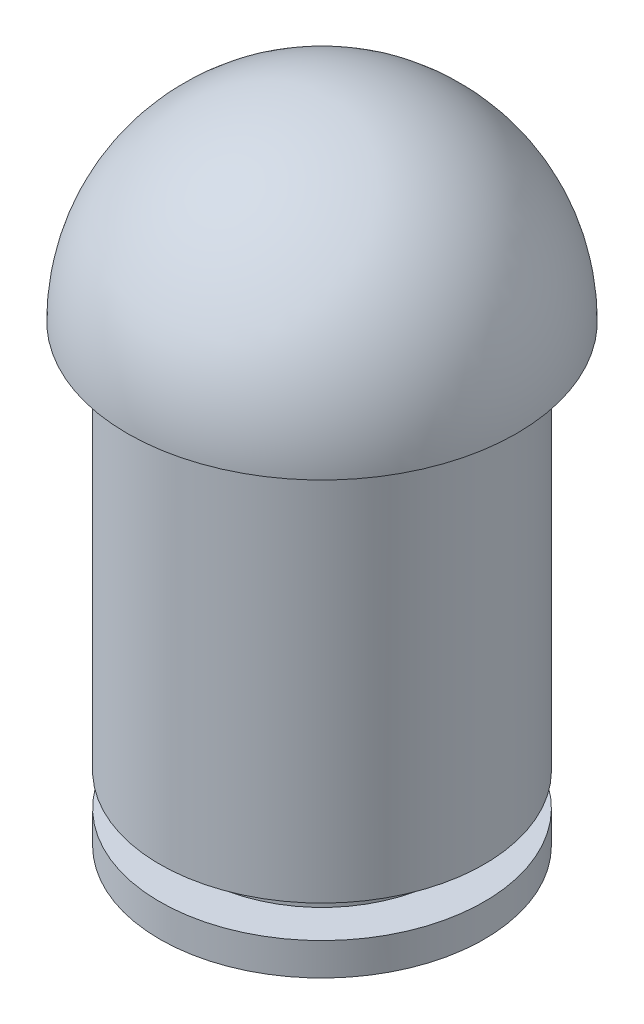
SolidWorks part; units mm, degrees
ref_plane "Front Plane" through (0, 0, 0) normal (0, 0, 1) x (1, 0, 0)
ref_plane "Top Plane" through (0, 0, 0) normal (0, 1, 0) x (1, 0, 0)
ref_plane "Right Plane" through (0, 0, 0) normal (1, 0, 0) x (0, 0, -1)
sketch "Sketch1" plane through (0, 0, 0) normal (0, 1, 0) x (1, 0, 0)
  circle A0 centre (0, 0) radius 2.5
extrude "Boss-Extrude1" add sketch "Sketch1" along normal blind 7
sketch "Sketch2" plane through (0, 0, 0) normal (0, 0, 1) x (1, 0, 0)
  line L0 (0, 7) -> (3, 7)
  line L1 (2.5, 7) -> (-2.5, 7) construction
  line L2 (0, 7) -> (0, 10)
  arc A0 (3, 7) -> (0, 10) centre (0, 7) ccw
revolve "Revolve1" add sketch "Sketch2" angle 360 about L2
sketch "Sketch3" plane through (0, 0, 0) normal (0, 0, 1) x (1, 0, 0)
  line L0 (0, 7) -> (0, 1)
  line L1 (-2.5, 7) -> (2.5, 7) construction
  line L2 (2.5, 1) -> (1.875, 1)
  line L3 (2.5, 0) -> (2.5, 7) construction
  line L4 (1.875, 1) -> (1.875, 0.5)
  line L5 (1.875, 0.5) -> (2.5, 0.5)
  line L6 (2.5, 0.5) -> (2.5, 1)
revolve "Cut-Revolve1" cut sketch "Sketch3" angle 360 about L0
